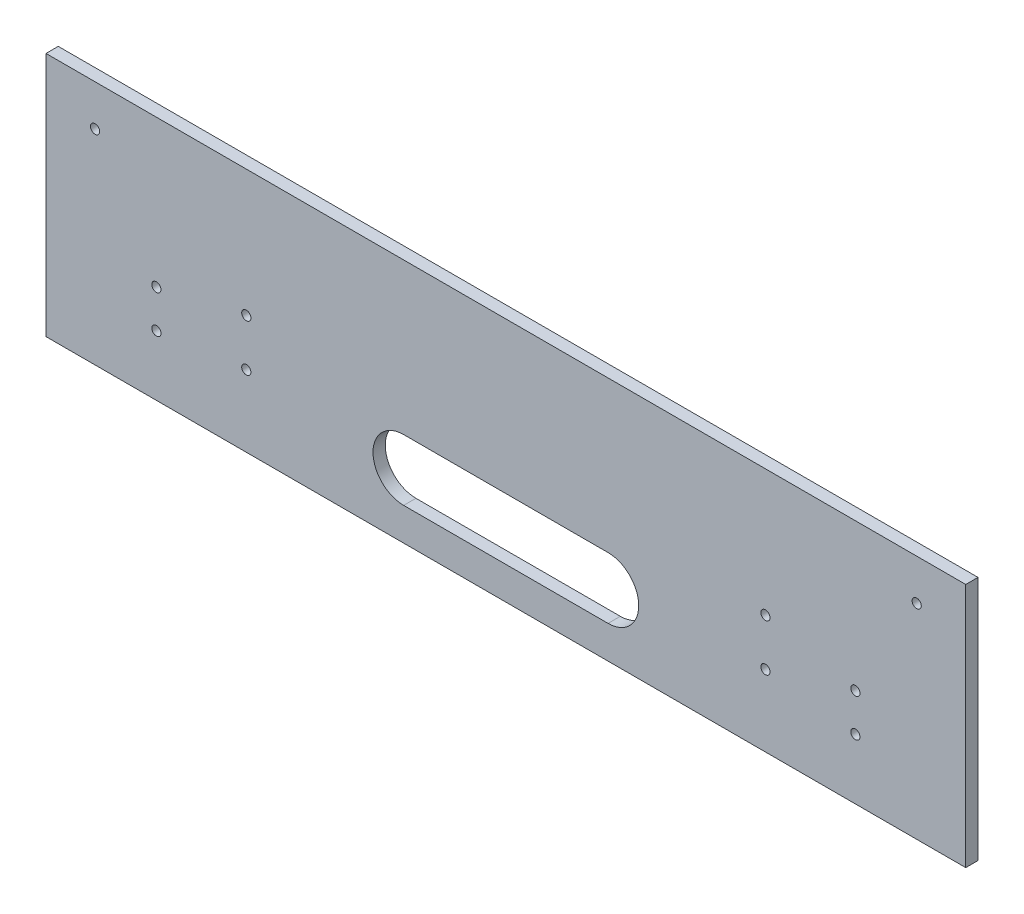
SolidWorks part; units mm, degrees
material "Pino"
ref_plane "Piano frontale" through (0, 0, 0) normal (0, 0, 1) x (1, 0, 0)
ref_plane "Piano superiore" through (0, 0, 0) normal (0, 1, 0) x (1, 0, 0)
ref_plane "Piano destro" through (0, 0, 0) normal (1, 0, 0) x (0, 0, -1)
sketch "Schizzo1" plane through (0, 0, 0) normal (0, 0, 1) x (1, 0, 0)
  line L1 (-225, 60) -> (225, 60)
  line L2 (-225, 60) -> (-225, -60)
  line L3 (-225, -60) -> (225, -60)
  line L4 (225, 60) -> (225, -60)
  line L5 (-225, 60) -> (225, -60) construction
  line L6 (-225, -60) -> (225, 60) construction
  point P4 (0, 0)
  dimension "D1" = 120
  dimension "D2" = 450
extrude "Estrusione-Estrusione1" add sketch "Schizzo1" along normal blind 6
sketch "Schizzo2" plane through (0, 0, 0) normal (0, 0, -1) x (-1, 0, 0)
  line L0 (0, 0) -> (0, -29) construction
  line L5 (225, -60) -> (-225, -60) construction
  line L6 (-50, -29) -> (50, -29) construction
  line L7 (-50, -14) -> (50, -14)
  line L8 (-50, -44) -> (50, -44)
  arc A0 (-50, -14) -> (-50, -44) centre (-50, -29) ccw
  arc A1 (50, -44) -> (50, -14) centre (50, -29) ccw
  point P11 (0, -29)
  dimension "D5" = 130
  dimension "D4" = 16
  dimension "D6" = 30
extrude "Taglio-Estrusione1" cut sketch "Schizzo2" against normal blind 10
sketch "Schizzo3" plane through (0, 0, 6) normal (0, 0, 1) x (1, 0, 0)
  line L0 (127, -25) -> (127, -2) construction
  line L1 (-225, -60) -> (225, -60) construction
  line L2 (225, -60) -> (225, 60) construction
  line L3 (-127, -2) -> (-127, -25) construction
  line L5 (-225, 60) -> (-225, -60) construction
  line L6 (-225, -60) -> (225, -60) construction
  circle A0 centre (-171, -12) radius 2.25
  circle A1 centre (-171, -30.5) radius 2.25
  circle A2 centre (171, -12) radius 2.25
  circle A3 centre (171, -30.5) radius 2.25
  circle A5 centre (201, 40) radius 2.25
  circle A7 centre (-201, 40) radius 2.25
  circle A8 centre (127, -2) radius 2.25
  circle A9 centre (127, -25) radius 2.25
  circle A10 centre (-127, -2) radius 2.25
  circle A11 centre (-127, -25) radius 2.25
  dimension "D1" = 4.5
  dimension "D5" = 4.5
  dimension "D2" = 23
  dimension "D3" = 58
  dimension "D4" = 98
  dimension "D6" = 98
  dimension "D7" = 58
extrude "Taglio-Estrusione2" cut sketch "Schizzo3" against normal blind 10
